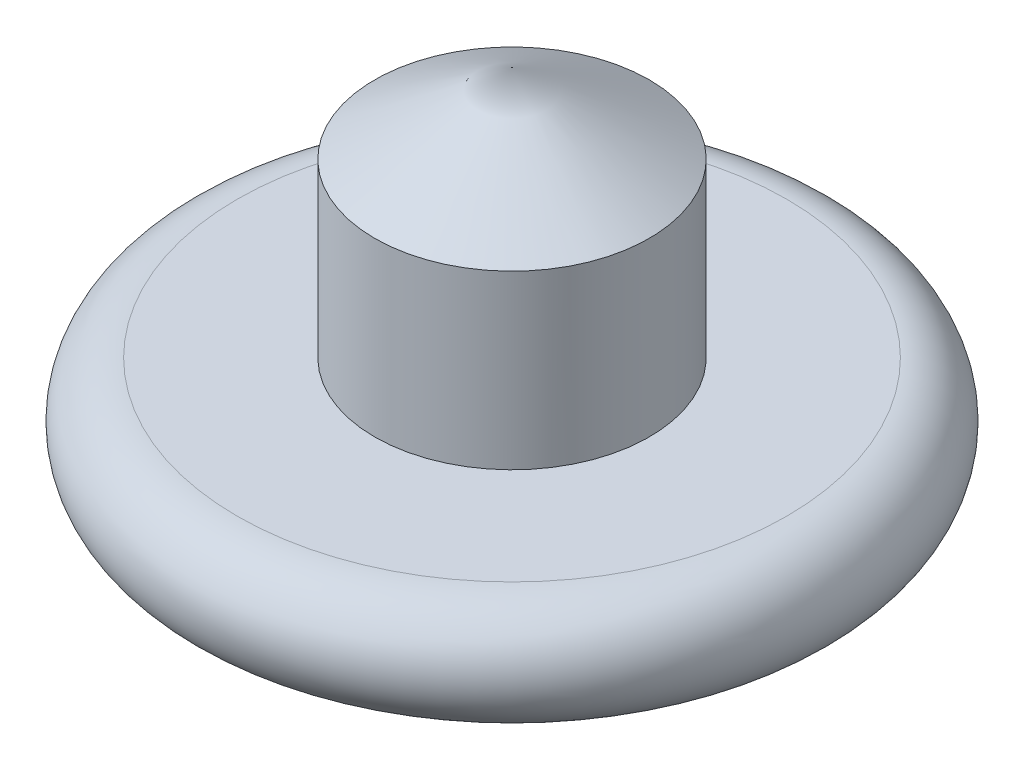
SolidWorks part; units mm, degrees
ref_plane "Front Plane" through (0, 0, 0) normal (0, 0, 1) x (1, 0, 0)
ref_plane "Top Plane" through (0, 0, 0) normal (0, 1, 0) x (1, 0, 0)
ref_plane "Right Plane" through (0, 0, 0) normal (1, 0, 0) x (0, 0, -1)
sketch "Sketch1" plane through (0, 0, 0) normal (0, 0, 1) x (1, 0, 0)
  line L0 (0, 0) -> (100, 0)
  line L3 (100, 40) -> (50, 40)
  line L4 (50, 102.6271) -> (0, 131.4946)
  line L5 (0, 131.4946) -> (0, 0)
  line L6 (50, 102.6271) -> (50, 40)
  arc A0 (100, 0) -> (100, 40) centre (100, 20) ccw
  dimension "D1" = 100
  dimension "D2" = 40
  dimension "D3" = 60
  dimension "D4" = 50
revolve "Revolve8" add sketch "Sketch1" angle 360 about L5
